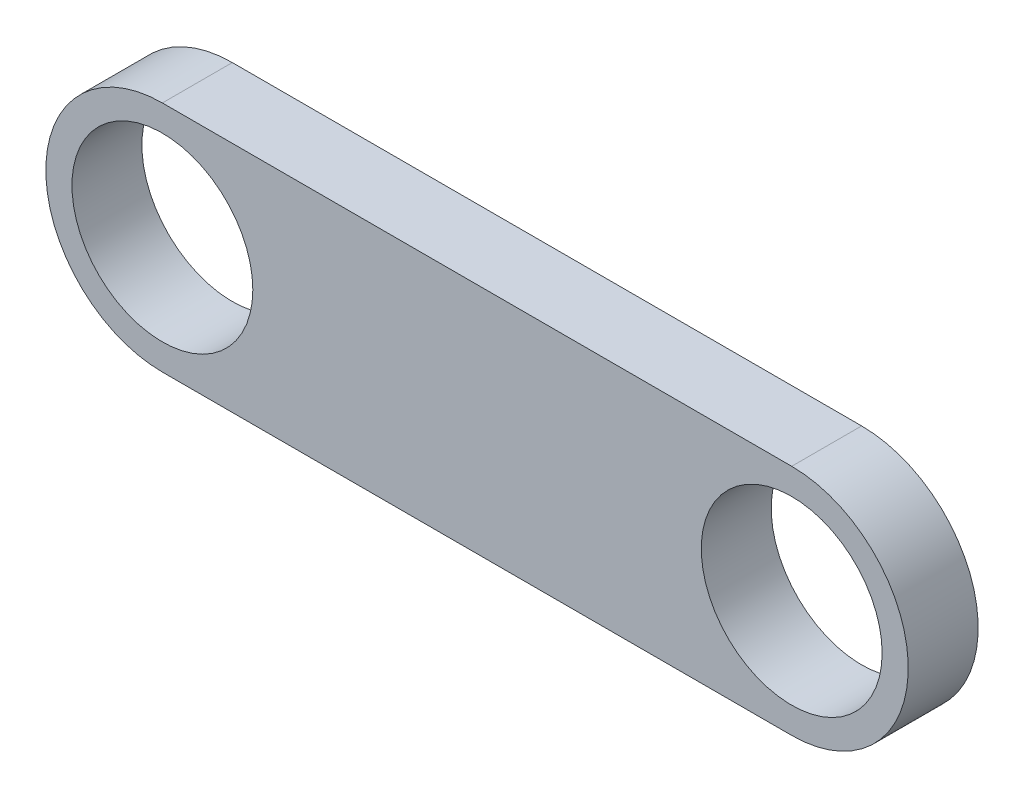
SolidWorks part; units mm, degrees
ref_plane "Front Plane" through (0, 0, 0) normal (0, 0, 1) x (1, 0, 0)
ref_plane "Top Plane" through (0, 0, 0) normal (0, 1, 0) x (1, 0, 0)
ref_plane "Right Plane" through (0, 0, 0) normal (1, 0, 0) x (0, 0, -1)
sketch "Sketch1" plane through (0, 0, 0) normal (0, 0, 1) x (1, 0, 0)
  line L1 (-12.202, -4.8946) -> (14.798, -4.8946)
  line L3 (-12.202, 5.1054) -> (14.798, 5.1054)
  arc A0 (-12.202, 5.1054) -> (-12.202, -4.8946) centre (-12.202, 0.1054) ccw
  arc A1 (14.798, 5.1054) -> (14.798, -4.8946) centre (14.798, 0.1054) cw
  circle A2 centre (-12.202, 0.1054) radius 3.88
  circle A3 centre (14.798, 0.1054) radius 3.88
  dimension "D3" = 7.76
  dimension "D4" = 7.76
  dimension "D1" = 10
  dimension "D2" = 27
extrude "Boss-Extrude1" add sketch "Sketch1" along normal blind 3
